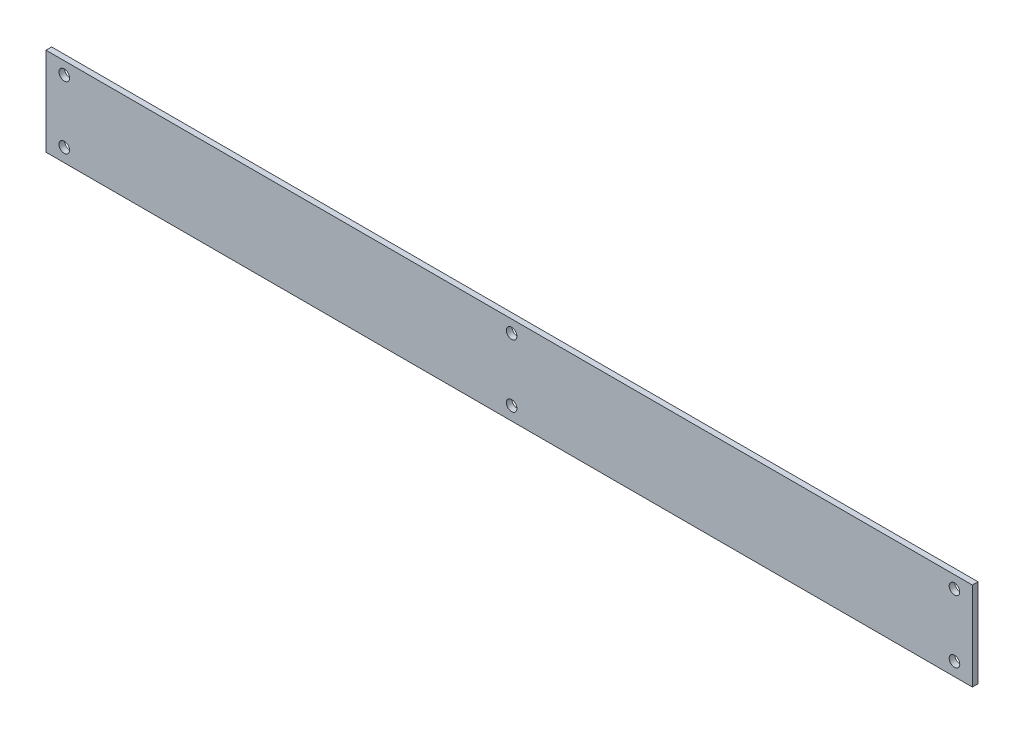
SolidWorks part; units mm, degrees
ref_plane "Plan de face" through (0, 0, 0) normal (0, 0, 1) x (1, 0, 0)
ref_plane "Plan de dessus" through (0, 0, 0) normal (0, 1, 0) x (1, 0, 0)
ref_plane "Plan de droite" through (0, 0, 0) normal (1, 0, 0) x (0, 0, -1)
sketch "Esquisse1" plane through (0, 0, 0) normal (0, 0, 1) x (1, 0, 0)
  line L1 (131.5, -12.55) -> (-131.5, -12.55)
  line L2 (131.5, -12.55) -> (131.5, 12.55)
  line L3 (131.5, 12.55) -> (-131.5, 12.55)
  line L4 (-131.5, -12.55) -> (-131.5, 12.55)
  line L5 (131.5, -12.55) -> (-131.5, 12.55) construction
  line L6 (131.5, 12.55) -> (-131.5, -12.55) construction
  point P0 (0, 0)
  dimension "D1" = 25.1
  dimension "D2" = 263
extrude "Boss.-Extru.1" add sketch "Esquisse1" along normal blind 1.6
sketch "Sketch1" plane through (0, 0, 1.6) normal (0, 0, 1) x (1, 0, 0)
  line L0 (-131.5, -12.55) -> (131.5, -12.55) construction
  line L1 (131.5, -12.55) -> (131.5, 12.55) construction
  line L2 (126.42, -8.74) -> (126.42, 12.55) construction
  line L3 (0.69, -8.74) -> (0.69, 6.0787) construction
  line L4 (126.42, -8.74) -> (111.862, -8.74) construction
  line L5 (126.42, 9.04) -> (116.6729, 9.04) construction
  line L6 (-126.31, -8.74) -> (-126.31, 2.6514) construction
  circle A0 centre (126.42, -8.74) radius 1.5
  circle A1 centre (126.42, 9.04) radius 1.5
  circle A2 centre (0.69, -8.74) radius 1.5
  circle A3 centre (-126.31, -8.74) radius 1.5
  circle A4 centre (0.69, 9.04) radius 1.5
  circle A5 centre (-126.31, 9.04) radius 1.5
  dimension "D4" = 130.81
  dimension "D1" = 3.81
  dimension "D2" = 21.59
  dimension "D3" = 5.08
  dimension "D5" = 257.81
extrude "Cut-Extrude1" cut sketch "Sketch1" against normal through all
